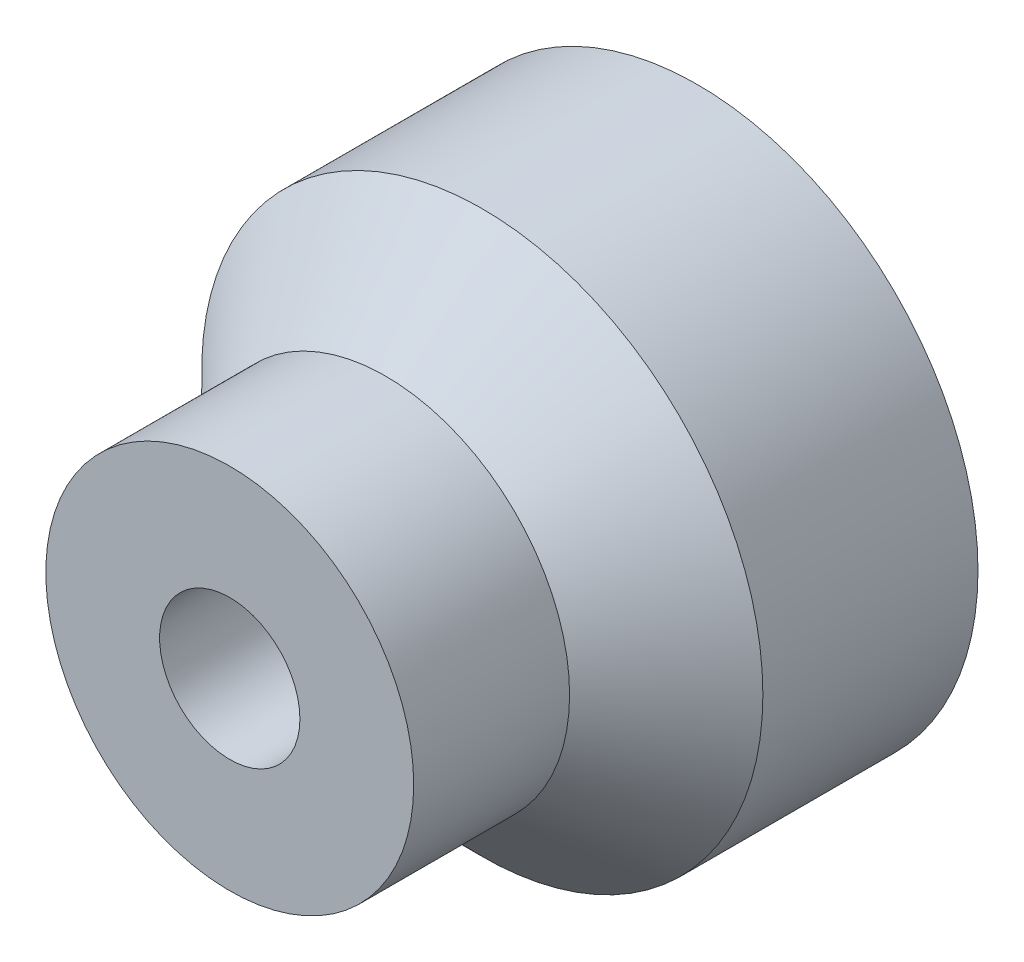
SolidWorks part; units mm, degrees
ref_plane "Front Plane" through (0, 0, 0) normal (0, 0, 1) x (1, 0, 0)
ref_plane "Top Plane" through (0, 0, 0) normal (0, 1, 0) x (1, 0, 0)
ref_plane "Right Plane" through (0, 0, 0) normal (1, 0, 0) x (0, 0, -1)
sketch "Sketch1" plane through (0, 0, 0) normal (0, 1, 0) x (1, 0, 0)
  line L0 (2.25, 0) -> (5.9, 0)
  line L1 (5.9, 0) -> (5.9, 5)
  line L2 (5.9, 5) -> (9, 8.1)
  line L3 (9, 8.1) -> (9, 15)
  line L4 (9, 15) -> (6, 15)
  line L5 (6, 15) -> (6, 10)
  line L6 (6, 10) -> (2.25, 10)
  line L7 (2.25, 10) -> (2.25, 0)
  line L8 (0, 0) -> (0, 15) construction
  point P11 (5.9, 2.5)
  point P12 (7.5, 7.0297)
  point P13 (0, 14)
  point P14 (0, 0)
  dimension "D1" = 4.5
  dimension "D2" = 11.8
  dimension "D3" = 12
  dimension "D4" = 5
  dimension "D5" = 5
  dimension "D6" = 10
  dimension "D7" = 18
  dimension "D8" = 45
revolve "Revolve1" add sketch "Sketch1" angle 360 about L8
